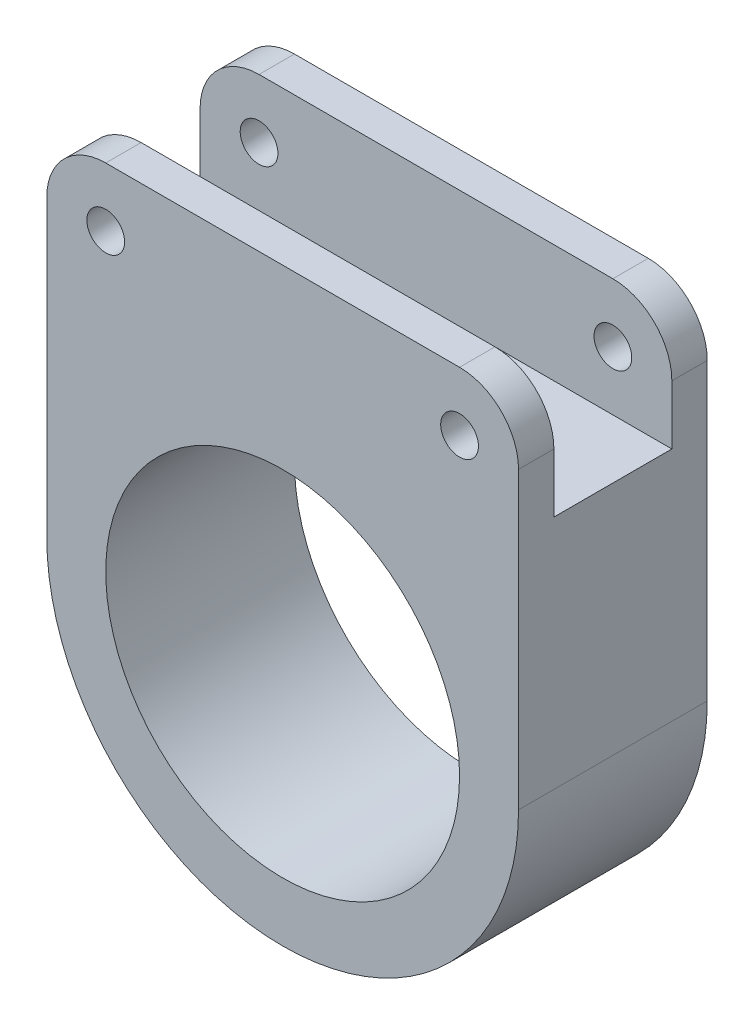
SolidWorks part; units mm, degrees
ref_plane "正面" through (0, 0, 0) normal (0, 0, 1) x (1, 0, 0)
ref_plane "平面" through (0, 0, 0) normal (0, 1, 0) x (1, 0, 0)
ref_plane "右側面" through (0, 0, 0) normal (1, 0, 0) x (0, 0, -1)
sketch "ｽｹｯﾁ1" plane through (0, 0, 0) normal (0, 0, 1) x (1, 0, 0)
  line L1 (-20, 25) -> (20, 25)
  line L2 (-20, 25) -> (-20, -25)
  line L3 (-20, -25) -> (20, -25)
  line L4 (20, 25) -> (20, -25)
  line L5 (-20, 25) -> (20, -25) construction
  line L6 (-20, -25) -> (20, 25) construction
  circle A0 centre (0, -5) radius 15
  circle A1 centre (-15, 20) radius 1.6
  circle A2 centre (15, 20) radius 1.6
  arc A3 (20, -5) -> (-20, -5) centre (0, -5) cw
  point P0 (0, 0)
  dimension "D3" = 5
  dimension "D4" = 30
  dimension "D5" = 5
  dimension "D6" = 5
  dimension "D7" = 5
  dimension "D8" = 3.2
  dimension "D9" = 5
  dimension "D10" = 3.2
  dimension "D1" = 50
  dimension "D2" = 40
extrude "ﾎﾞｽ - 押し出し1" add sketch "ｽｹｯﾁ1" along normal blind 16 contours A3 L4 L1 L2 A2 A1 A0
sketch "ｽｹｯﾁ2" plane through (0, 25, 0) normal (0, 1, 0) x (1, 0, 0)
  line L1 (-20, -3) -> (20, -3)
  line L2 (-20, -3) -> (-20, -13)
  line L3 (-20, -13) -> (20, -13)
  line L4 (20, -3) -> (20, -13)
  line L5 (-20, -3) -> (20, -13) construction
  line L6 (-20, -13) -> (20, -3) construction
  point P0 (0, -8)
  dimension "D2" = 10
  dimension "D3" = 40
extrude "ｶｯﾄ - 押し出し1" cut sketch "ｽｹｯﾁ2" against normal blind 10
fillet "ﾌｨﾚｯﾄ2" radius 5 4 edges at (20, 25, 14.5) (20, 25, 1.5) (-20, 25, 1.5) (-20, 25, 14.5)
